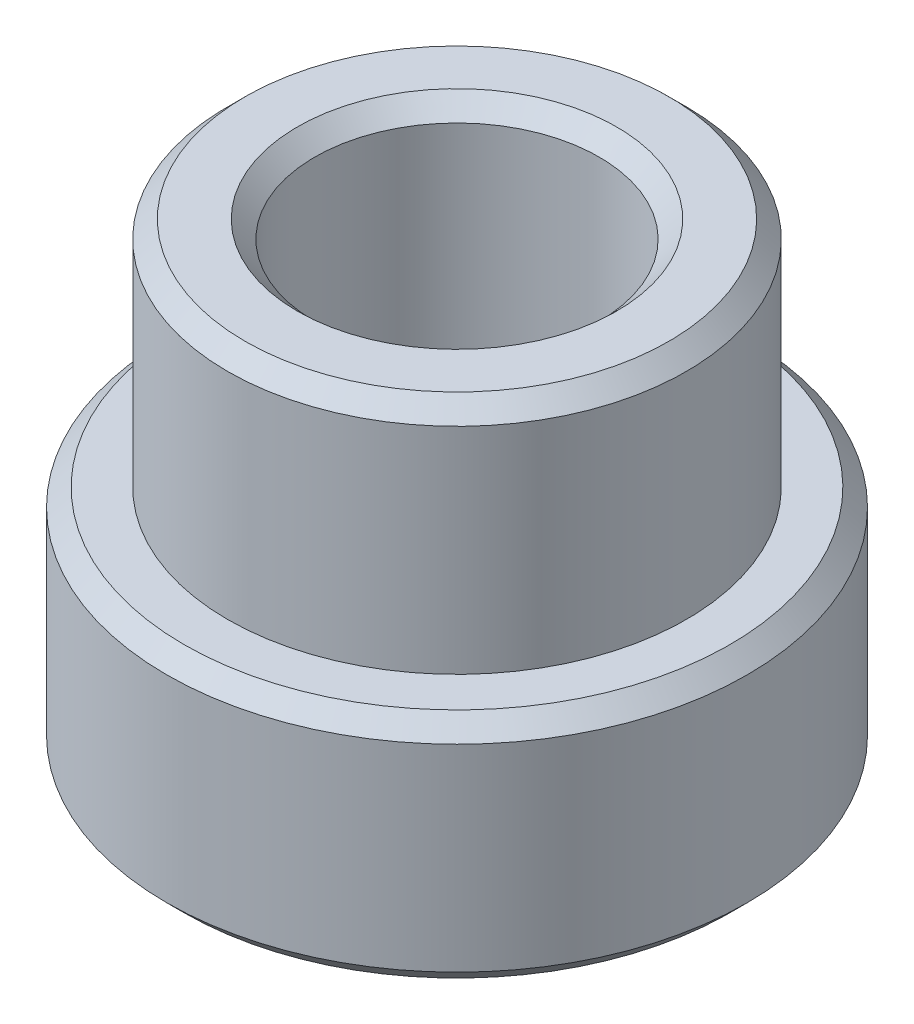
SolidWorks part; units mm, degrees
ref_plane "Front Plane" through (0, 0, 0) normal (0, 0, 1) x (1, 0, 0)
ref_plane "Top Plane" through (0, 0, 0) normal (0, 1, 0) x (1, 0, 0)
ref_plane "Right Plane" through (0, 0, 0) normal (1, 0, 0) x (0, 0, -1)
sketch "Sketch1" plane through (0, 0, 0) normal (0, 1, 0) x (1, 0, 0)
  circle A0 centre (0, 0) radius 5
  circle A1 centre (0, 0) radius 2.45
  dimension "D1" = 10
  dimension "D2" = 4.9
extrude "Boss-Extrude1" add sketch "Sketch1" along normal blind 8
sketch "Sketch2" plane through (0, 8, 0) normal (0, 1, 0) x (1, 0, 0)
  circle A0 centre (0, 0) radius 3.95
  circle A1 centre (0, 0) radius 10
  dimension "D1" = 7.9
  dimension "D2" = 20
extrude "Cut-Extrude1" cut sketch "Sketch2" along direction (0, 1, 0) on the side against the normal offset from surface (4 mm away) 4
chamfer "Chamfer1" distance 0.3 angle 45 5 edges at (0, 0, 2.45) (0, 0, 5) (0, 4, 5) (0, 8, 2.45) (0, 8, 3.95)
